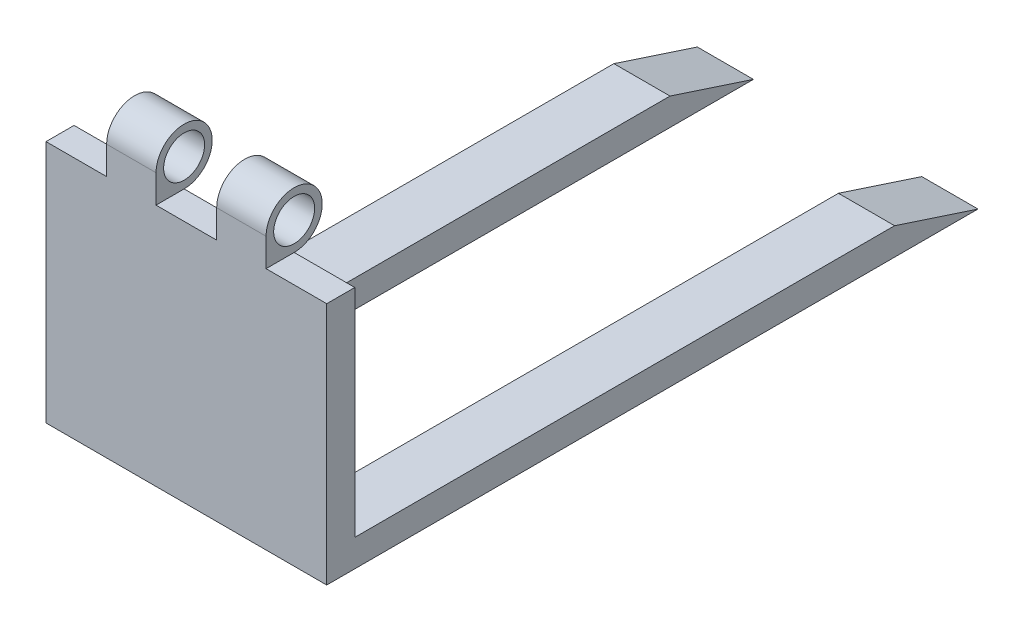
SolidWorks part; units mm, degrees
material "Brass"
ref_plane "Front Plane" through (0, 0, 0) normal (0, 0, 1) x (1, 0, 0)
ref_plane "Top Plane" through (0, 0, 0) normal (0, 1, 0) x (1, 0, 0)
ref_plane "Right Plane" through (0, 0, 0) normal (1, 0, 0) x (0, 0, -1)
sketch "Sketch1" plane through (0, 0, 0) normal (1, 0, 0) x (0, 0, -1)
  line L1 (0, 0) -> (-6.35, 0)
  line L2 (0, 0) -> (0, 61.468)
  line L3 (0, 61.468) -> (-6.35, 61.468)
  line L4 (-6.35, 0) -> (-6.35, 61.468)
  dimension "D1" = 61.468
  dimension "D2" = 6.35
extrude "Boss-Extrude1" add sketch "Sketch1" along normal mid plane 63.5
sketch "Sketch4" plane through (31.75, 0, 0) normal (1, 0, 0) x (0, 0, -1)
  line L0 (-6.35, 0) -> (140.97, 0)
  line L1 (140.97, 0) -> (122.102, 6.168)
  line L2 (122.102, 6.168) -> (-6.35, 6.168)
  line L3 (-6.35, 61.468) -> (-6.35, 0) construction
  line L4 (-6.35, 6.168) -> (-6.35, 0)
  dimension "D1" = 147.32
extrude "Boss-Extrude2" add sketch "Sketch4" against normal blind 12.7
mirror "Mirror1" about plane through (0, 0, 0) normal (1, 0, 0) of "Boss-Extrude2"
sketch "Sketch7" plane through (31.75, 0, 0) normal (1, 0, 0) x (0, 0, -1)
  circle A0 centre (0, 61.468) radius 6.35
sweep "Sweep1" add profiles "Sketch7" path edge at (0, 61.468, 0)
sketch "Sketch8" plane through (31.75, 0, 0) normal (1, 0, 0) x (0, 0, -1)
  circle A0 centre (0, 61.468) radius 4.6355
  dimension "D1" = 9.271
extrude "Cut-Extrude1" cut sketch "Sketch8" against normal through all
sketch "Sketch12" plane through (0, 0, 6.35) normal (0, 0, 1) x (1, 0, 0)
  line L0 (0, 166.9924) -> (0, -31.3564) construction
  line L2 (-31.75, 67.818) -> (-18.034, 67.818)
  line L3 (-31.75, 67.818) -> (-31.75, 55.118)
  line L4 (-31.75, 55.118) -> (-18.034, 55.118)
  line L5 (-18.034, 67.818) -> (-18.034, 55.118)
  line L6 (31.75, 55.118) -> (18.034, 55.118)
  line L7 (18.034, 67.818) -> (18.034, 55.118)
  line L8 (31.75, 67.818) -> (18.034, 67.818)
  line L9 (31.75, 67.818) -> (31.75, 55.118)
  line L10 (31.75, 67.818) -> (-31.75, 67.818) construction
  line L11 (-6.858, 67.818) -> (6.858, 67.818)
  line L12 (-6.858, 67.818) -> (-6.858, 55.118)
  line L13 (-6.858, 55.118) -> (6.858, 55.118)
  line L14 (6.858, 67.818) -> (6.858, 55.118)
  point P18 (0, 67.818)
  dimension "D1" = 13.716
  dimension "D2" = 12.7
  dimension "D3" = 13.716
  dimension "D4" = 12.7
extrude "Cut-Extrude2" cut sketch "Sketch12" against normal through all both and the other way through all
